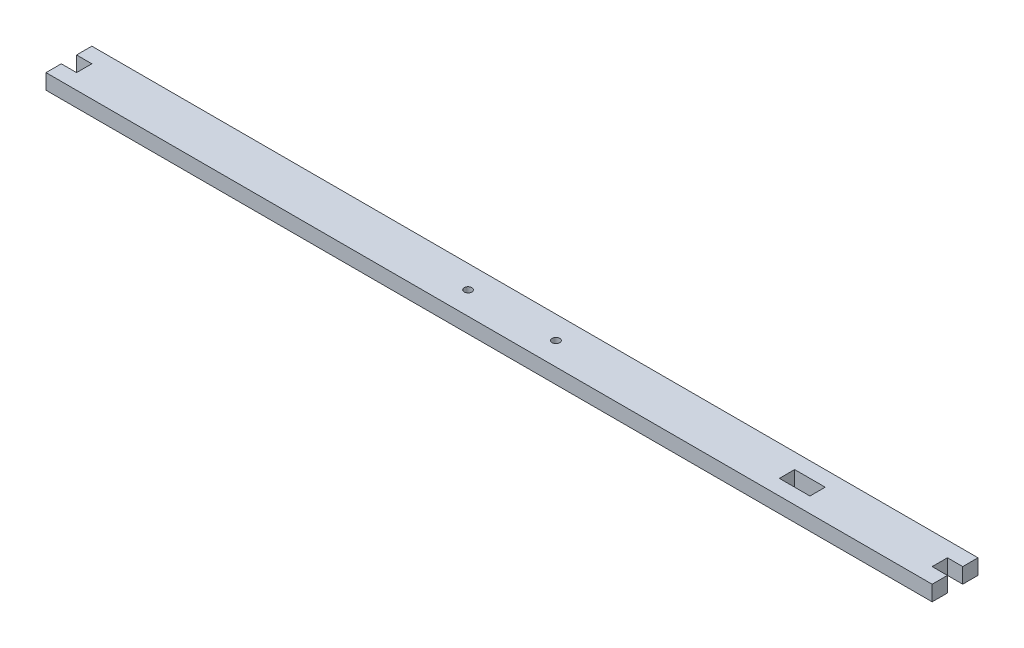
SolidWorks part; units mm, degrees
material "Mahogany"
ref_plane "Front" through (0, 0, 0) normal (0, 0, 1) x (1, 0, 0)
ref_plane "Top" through (0, 0, 0) normal (0, 1, 0) x (1, 0, 0)
ref_plane "Right" through (0, 0, 0) normal (1, 0, 0) x (0, 0, -1)
sketch "Sketch1" plane through (0, 0, 0) normal (0, 1, 0) x (1, 0, 0)
  line L0 (177.8, 19.05) -> (177.8, 0) construction
  line L1 (0, 0) -> (355.6, 0)
  line L2 (0, 0) -> (0, 19.05)
  line L3 (0, 19.05) -> (355.6, 19.05)
  line L4 (355.6, 0) -> (355.6, 19.05)
  line L5 (0, 19.05) -> (-6.35, 19.05)
  line L6 (0, 19.05) -> (0, 12.7)
  line L7 (0, 12.7) -> (-6.35, 12.7)
  line L8 (-6.35, 19.05) -> (-6.35, 12.7)
  line L9 (0, 0) -> (-6.35, 0)
  line L10 (0, 0) -> (0, 6.35)
  line L11 (0, 6.35) -> (-6.35, 6.35)
  line L12 (-6.35, 0) -> (-6.35, 6.35)
  line L13 (361.95, 0) -> (361.95, 6.35)
  line L14 (355.6, 6.35) -> (361.95, 6.35)
  line L15 (355.6, 0) -> (355.6, 6.35)
  line L16 (355.6, 0) -> (361.95, 0)
  line L17 (361.95, 19.05) -> (361.95, 12.7)
  line L18 (355.6, 12.7) -> (361.95, 12.7)
  line L19 (355.6, 19.05) -> (355.6, 12.7)
  line L20 (355.6, 19.05) -> (361.95, 19.05)
  line L21 (159.5437, 9.525) -> (196.0562, 9.525) construction
  line L23 (292.1, 12.7) -> (304.8, 12.7)
  line L24 (292.1, 12.7) -> (292.1, 6.35)
  line L25 (292.1, 6.35) -> (304.8, 6.35)
  line L26 (304.8, 12.7) -> (304.8, 6.35)
  circle A0 centre (159.5437, 9.525) radius 1.5875
  circle A1 centre (196.0562, 9.525) radius 1.5875
  point P23 (177.8, 9.525)
  point P24 (177.8, 9.525)
  point P29 (0, 0)
  dimension "D5" = 36.5125
  dimension "D6" = 3.175
  dimension "D1" = 19.05
  dimension "D2" = 355.6
  dimension "D3" = 6.35
  dimension "D4" = 6.35
  dimension "D7" = 50.8
  dimension "D8" = 12.7
extrude "Boss-Extrude1" add sketch "Sketch1" along normal blind 6.35 contours L0 L3 L2 L1 | L3 L0 L1 L4 | L4 L16 L13 L14 | L20 L4 L18 L17 | L5 L8 L7 L2 | L12 L9 L2 L11
